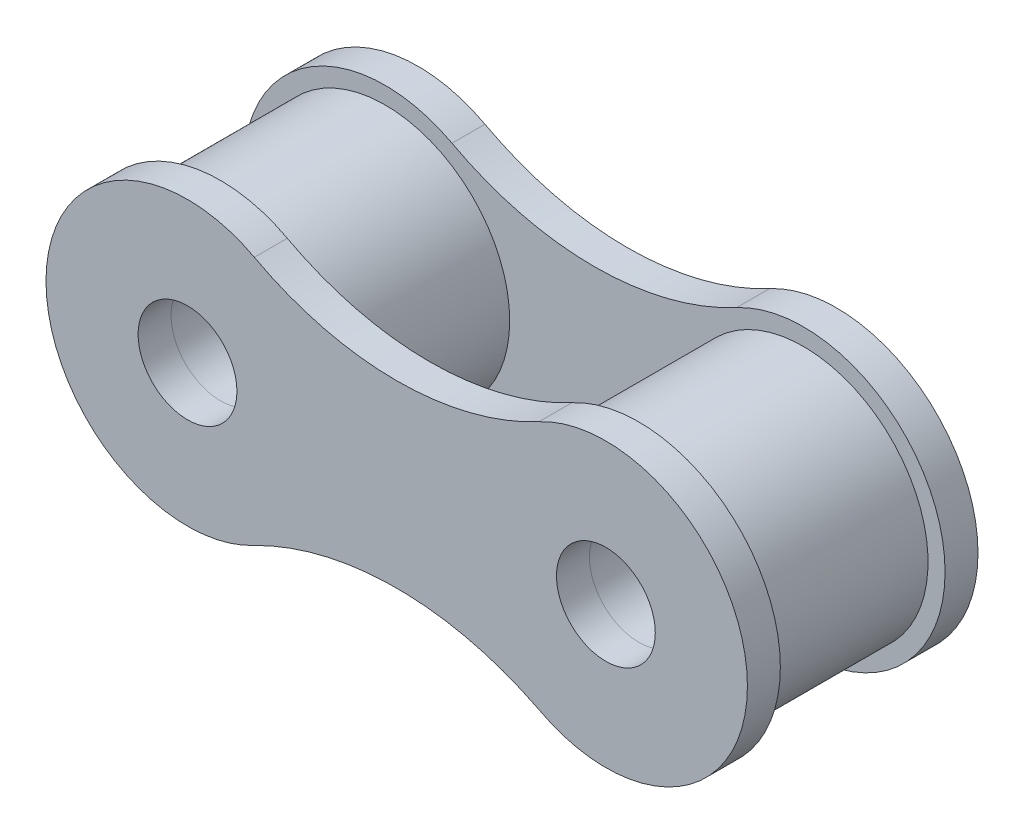
SolidWorks part; units mm, degrees
ref_plane "Front Plane" through (0, 0, 0) normal (0, 0, 1) x (1, 0, 0)
ref_plane "Top Plane" through (0, 0, 0) normal (0, 1, 0) x (1, 0, 0)
ref_plane "Right Plane" through (0, 0, 0) normal (1, 0, 0) x (0, 0, -1)
sketch "Sketch1" plane through (0, 0, 0) normal (0, 0, 1) x (1, 0, 0)
  circle A0 centre (-6.35, 0) radius 1.5119
  circle A1 centre (-6.35, 0) radius 3.7798
  circle A2 centre (6.35, 0) radius 3.7798
  circle A3 centre (6.35, 0) radius 1.5119
  dimension "D1" = 12.7
  dimension "D2" = 6.35
extrude "Boss-Extrude1" add sketch "Sketch1" along normal mid plane 5
sketch "Sketch2" plane through (0, 0, -2.5) normal (0, 0, 1) x (1, 0, 0)
  arc A0 (-4.3211, 3.7871) -> (-4.3211, -3.7871) centre (-6.35, 0) ccw
  arc A1 (4.3211, 3.7871) -> (4.3211, -3.7871) centre (6.35, 0) cw
  arc A2 (-4.3211, 3.7871) -> (4.3211, 3.7871) centre (0, 11.8527) ccw
  arc A3 (-4.3211, -3.7871) -> (4.3211, -3.7871) centre (0, -12.2708) cw
  circle A4 centre (6.35, 0) radius 1.5
  circle A5 centre (-6.35, 0) radius 1.5
  dimension "D1" = 12.7
  dimension "D2" = 6.35
extrude "Boss-Extrude2" add sketch "Sketch2" against normal blind 1
ref_plane "Plane1" through (0, 0, 2.5) normal (0, 0, 1) x (1, 0, 0)
mirror "Mirror1" about plane through (0, 0, 0) normal (0, 0, 1) of "Boss-Extrude2"
